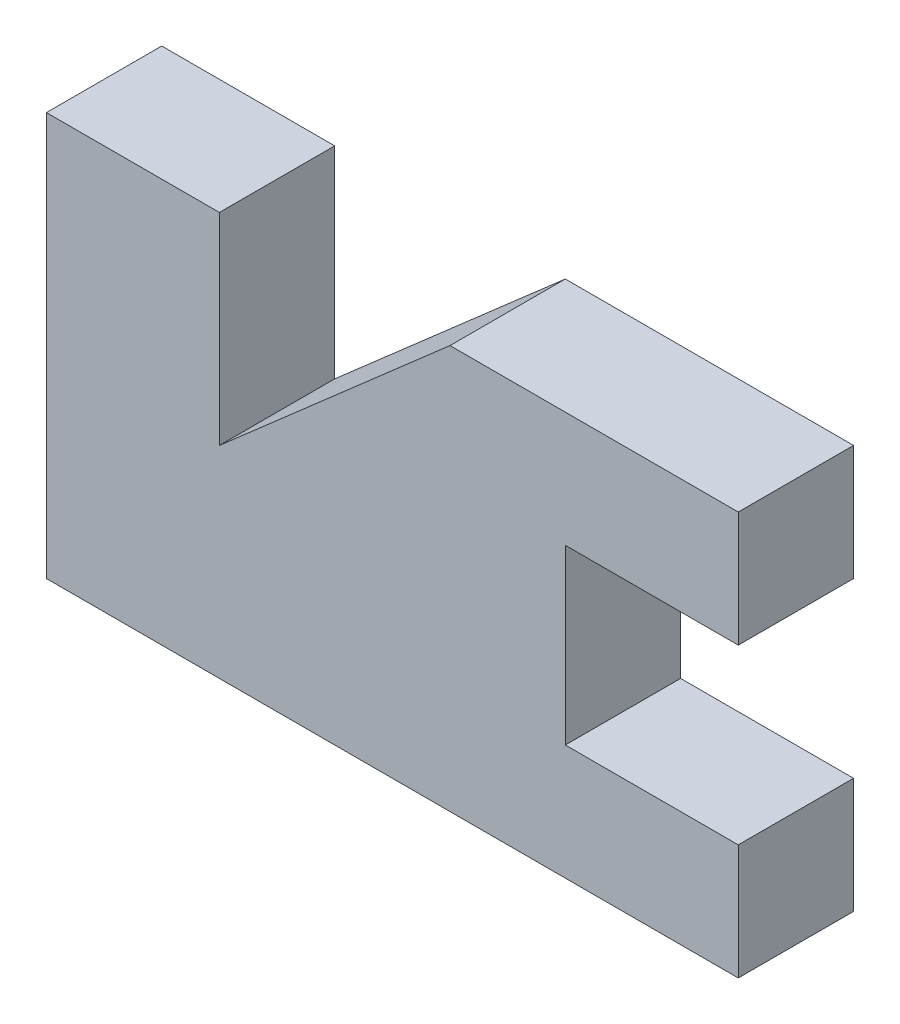
SolidWorks part; units mm, degrees
ref_plane "Front Plane" through (0, 0, 0) normal (0, 0, 1) x (1, 0, 0)
ref_plane "Top Plane" through (0, 0, 0) normal (0, 1, 0) x (1, 0, 0)
ref_plane "Right Plane" through (0, 0, 0) normal (1, 0, 0) x (0, 0, -1)
sketch "Sketch1" plane through (0, 0, 0) normal (0, 0, 1) x (1, 0, 0)
  line L0 (300, 75) -> (150, 75)
  line L1 (-300, -175) -> (300, -175)
  line L2 (-300, -175) -> (-300, 175)
  line L3 (-300, 175) -> (-150, 175)
  line L4 (300, -175) -> (300, -75)
  line L7 (150, 75) -> (150, -75)
  line L8 (150, -75) -> (300, -75)
  line L9 (-150, 175) -> (-150, 0)
  line L10 (-150, 0) -> (50, 175)
  line L11 (50, 175) -> (300, 175)
  line L12 (300, 75) -> (300, 175)
  point P0 (0, 0)
  dimension "D1" = 600
  dimension "D2" = 350
  dimension "D3" = 175
  dimension "D4" = 150
  dimension "D5" = 150
  dimension "D6" = 150
  dimension "D7" = 100
  dimension "D8" = 200
extrude "Boss-Extrude1" add sketch "Sketch1" along normal blind 100
